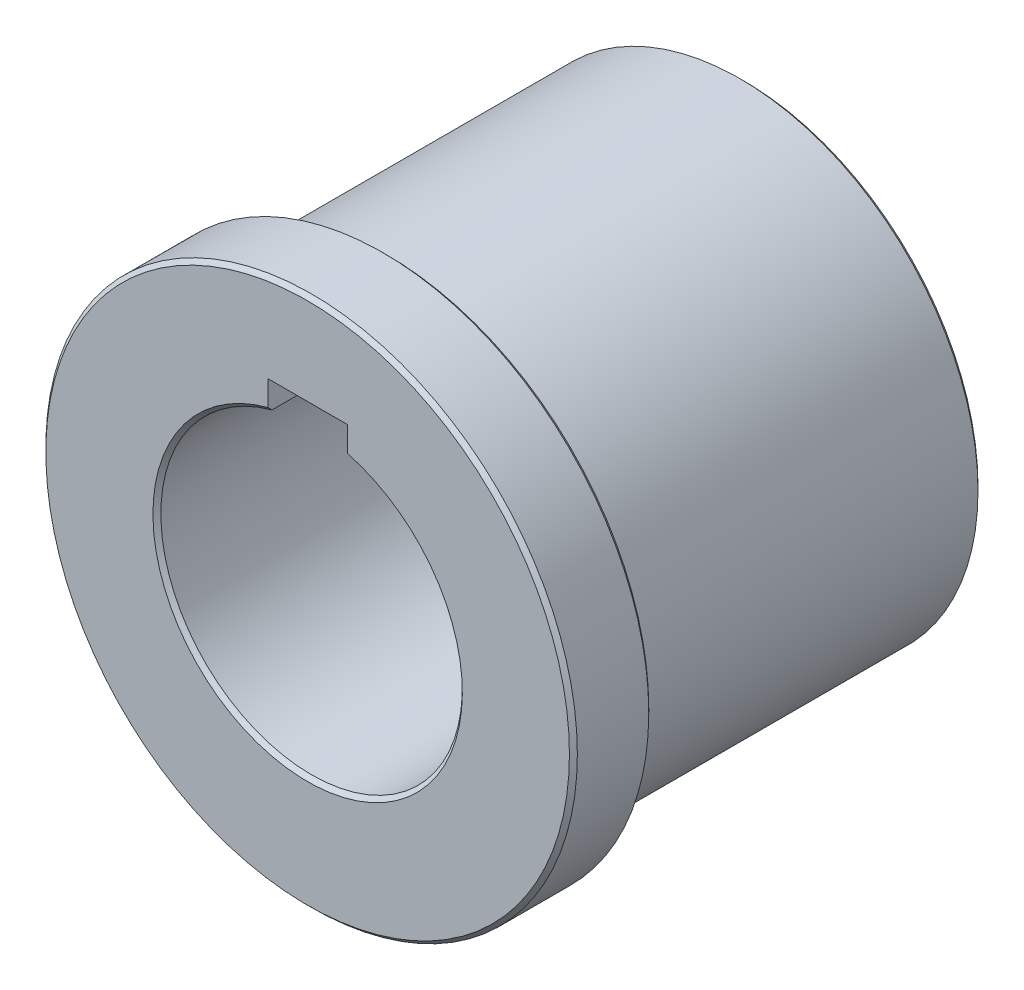
SolidWorks part; units mm, degrees
ref_plane "前视基准面" through (0, 0, 0) normal (0, 0, 1) x (1, 0, 0)
ref_plane "上视基准面" through (0, 0, 0) normal (0, 1, 0) x (1, 0, 0)
ref_plane "右视基准面" through (0, 0, 0) normal (1, 0, 0) x (0, 0, -1)
sketch "草图1" plane through (0, 0, 0) normal (0, 0, 1) x (1, 0, 0)
  circle A0 centre (0, 0) radius 30
  circle A1 centre (0, 0) radius 19
  dimension "D1" = 60
extrude "拉伸1" add sketch "草图1" along normal blind 55
sketch "草图2" plane through (0, 0, 55) normal (0, 0, 1) x (1, 0, 0)
  line L2 (5, 19) -> (5, 18.3303)
  line L3 (5, 19) -> (5, 22)
  line L4 (-5, 19) -> (-5, 18.3303)
  line L5 (-5, 19) -> (-5, 22)
  line L7 (-5, 22) -> (5, 22)
  arc A1 (5, 18.3303) -> (-5, 18.3303) centre (0, 0) ccw
extrude "切除-拉伸1" cut sketch "草图2" against normal through all
sketch "草图3" plane through (0, 0, 55) normal (0, 0, 1) x (1, 0, 0)
  circle A0 centre (0, 0) radius 27.5
  circle A1 centre (0, 0) radius 33.5
extrude "拉伸2" add sketch "草图3" against normal blind 10
sketch "草图4" plane through (0, 0, 0) normal (0, 0, -1) x (-1, 0, 0)
  circle A1 centre (12.5, 21.6506) radius 2.5
  circle A2 centre (25, 0) radius 2.5
  circle A3 centre (12.5, -21.6506) radius 2.5
  circle A4 centre (-12.5, -21.6506) radius 2.5
  circle A5 centre (-25, 0) radius 2.5
  circle A6 centre (-12.5, 21.6506) radius 2.5
  dimension "D1" = 5
extrude "切除-拉伸2" cut sketch "草图4" against normal blind 34
chamfer "倒角1" distance 0.5 angle 45 5 edges at (0, -19, 55) (33.5, 0, 45) (33.5, 0, 55) (0, -19, 0) (30, 0, 0)
